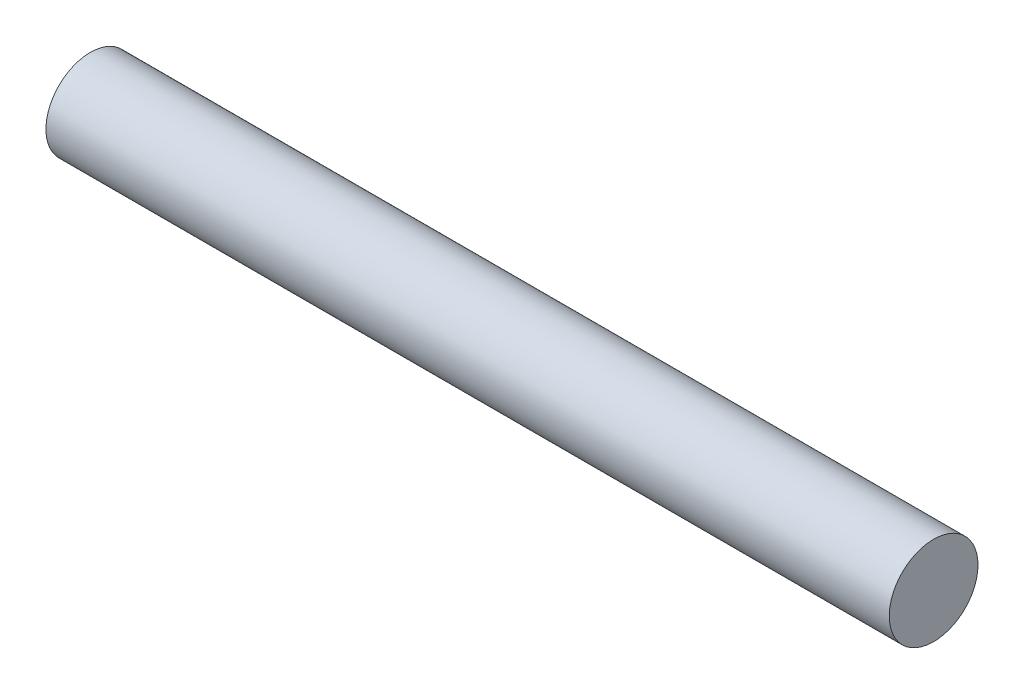
SolidWorks part; units mm, degrees
ref_plane "Front Plane" through (0, 0, 0) normal (0, 0, 1) x (1, 0, 0)
ref_plane "Top Plane" through (0, 0, 0) normal (0, 1, 0) x (1, 0, 0)
ref_plane "Right Plane" through (0, 0, 0) normal (1, 0, 0) x (0, 0, -1)
sketch "Sketch1" plane through (0, 0, 0) normal (1, 0, 0) x (0, 0, -1)
  circle A0 centre (0, 0) radius 20
  dimension "D1" = 40
extrude "Boss-Extrude1" add sketch "Sketch1" along normal blind 380
